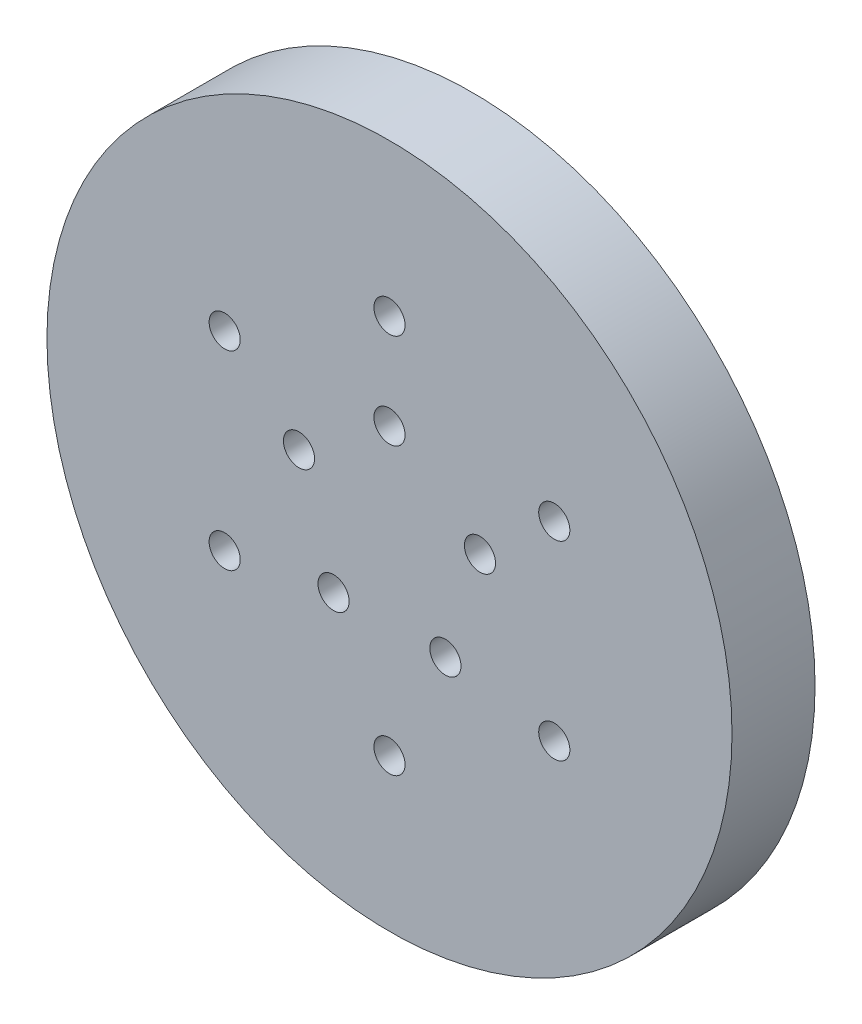
SolidWorks part; units mm, degrees
ref_plane "Front" through (0, 0, 0) normal (0, 0, 1) x (1, 0, 0)
ref_plane "Top" through (0, 0, 0) normal (0, 1, 0) x (1, 0, 0)
ref_plane "Right" through (0, 0, 0) normal (1, 0, 0) x (0, 0, -1)
sketch "Sketch1" plane through (0, 0, 0) normal (0, 0, 1) x (1, 0, 0)
  circle A0 centre (0, 0) radius 16.5
  dimension "D1" = 33
extrude "Boss-Extrude1" add sketch "Sketch1" along normal blind 4
sketch "Sketch2" plane through (0, 0, 4) normal (0, 0, 1) x (1, 0, 0)
  circle A0 centre (0, 9.1664) radius 0.75
  circle A1 centre (7.9384, 4.5832) radius 0.75
  circle A2 centre (7.9384, -4.5832) radius 0.75
  circle A3 centre (0, -9.1664) radius 0.75
  circle A4 centre (-7.9384, -4.5832) radius 0.75
  circle A5 centre (-7.9384, 4.5832) radius 0.75
  circle A6 centre (0, 4.5832) radius 0.75
  circle A7 centre (4.3589, 1.4163) radius 0.75
  circle A8 centre (2.694, -3.7079) radius 0.75
  circle A9 centre (-2.694, -3.7079) radius 0.75
  circle A10 centre (-4.3589, 1.4163) radius 0.75
  point P15 (0, 0)
  point P25 (0, 0)
  dimension "D1" = 6
  dimension "D2" = 5
extrude "Cut-Extrude1" cut sketch "Sketch2" against normal through all
